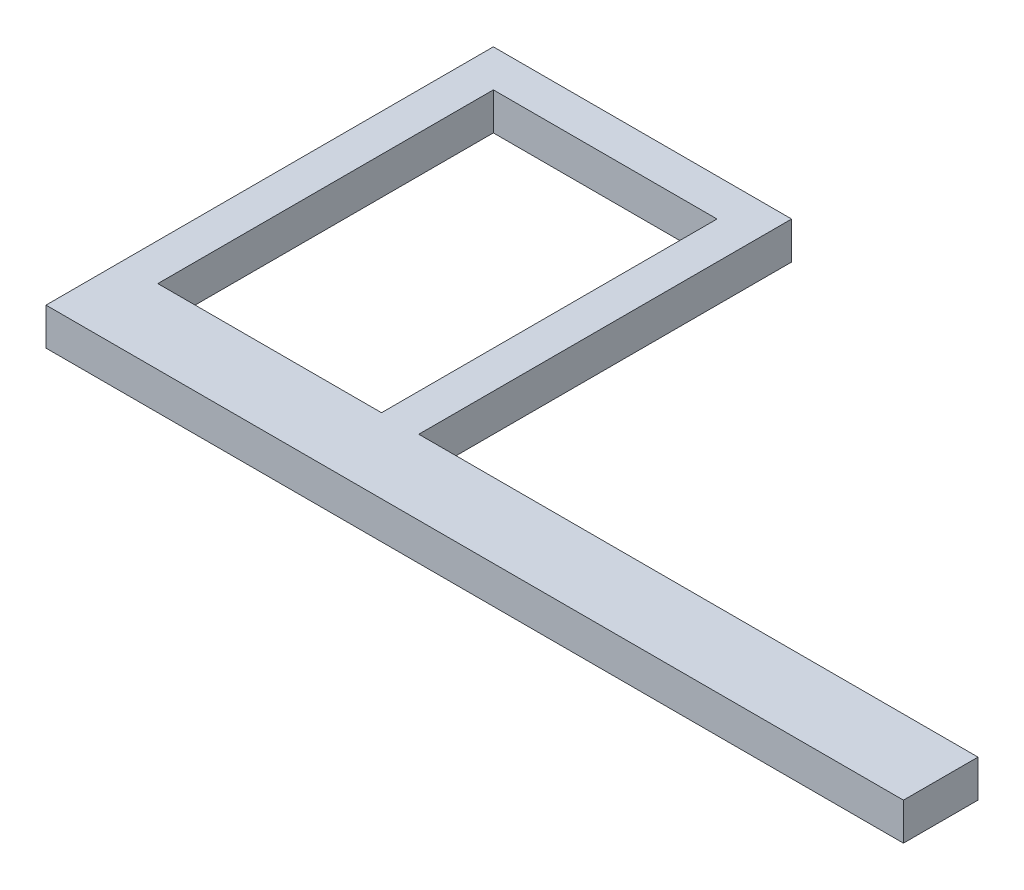
SolidWorks part; units mm, degrees
ref_plane "Plan de face" through (0, 0, 0) normal (0, 0, 1) x (1, 0, 0)
ref_plane "Plan de dessus" through (0, 0, 0) normal (0, 1, 0) x (1, 0, 0)
ref_plane "Plan de droite" through (0, 0, 0) normal (1, 0, 0) x (0, 0, -1)
sketch "Esquisse1" plane through (0, 0, 0) normal (0, 1, 0) x (1, 0, 0)
  line L0 (-109.9051, 48.4015) -> (-109.9051, -11.5985)
  line L1 (-109.9051, -11.5985) -> (5.0949, -11.5985)
  line L2 (5.0949, -11.5985) -> (5.0949, -1.5985)
  line L3 (5.0949, -1.5985) -> (-69.9051, -1.5985)
  line L4 (-69.9051, -1.5985) -> (-69.9051, 48.4015)
  line L5 (-69.9051, 48.4015) -> (-109.9051, 48.4015)
  dimension "D1" = 40
  dimension "D2" = 60
  dimension "D3" = 10
  dimension "D4" = 75
extrude "Boss.-Extru.1" add sketch "Esquisse1" along normal blind 5
sketch "Esquisse7" plane through (0, 5, 0) normal (0, 1, 0) x (1, 0, 0)
  line L0 (-109.9051, -11.5985) -> (5.0949, -11.5985) construction
  line L1 (-104.9051, 43.4015) -> (-74.9051, 43.4015)
  line L2 (-104.9051, 43.4015) -> (-104.9051, -1.5985)
  line L3 (-104.9051, -1.5985) -> (-74.9051, -1.5985)
  line L4 (-74.9051, 43.4015) -> (-74.9051, -1.5985)
  line L5 (-69.9051, 48.4015) -> (-109.9051, 48.4015) construction
  line L6 (-69.9051, -1.5985) -> (-69.9051, 48.4015) construction
  line L7 (-109.9051, 48.4015) -> (-109.9051, -11.5985) construction
  dimension "D1" = 10
  dimension "D2" = 5
  dimension "D3" = 5
  dimension "D4" = 5
extrude "Enlèv. mat.-Extru.2" cut sketch "Esquisse7" against normal through all
